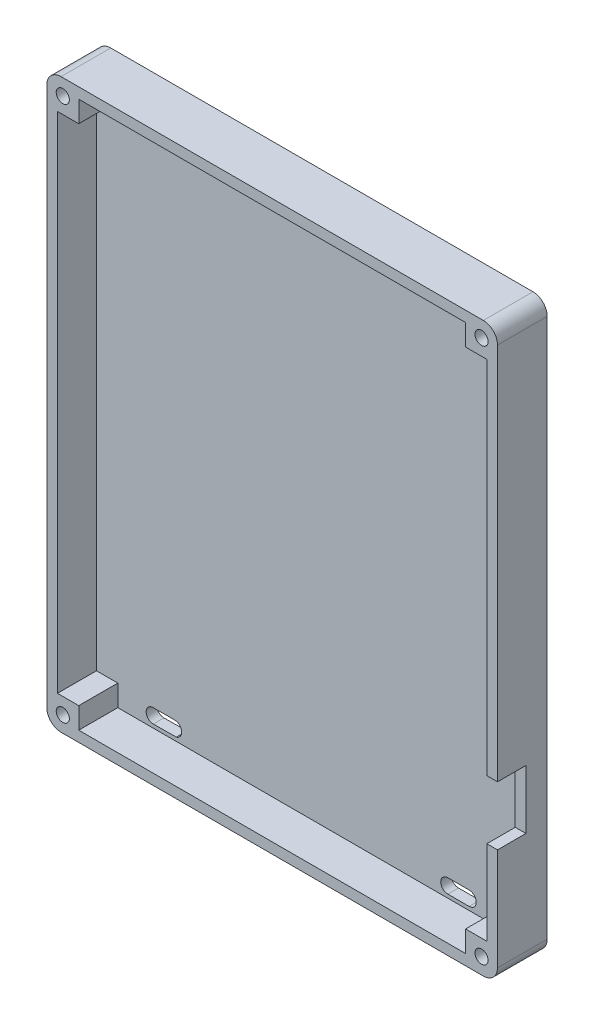
SolidWorks part; units mm, degrees
ref_plane "Ön Düzlem" through (0, 0, 0) normal (0, 0, 1) x (1, 0, 0)
ref_plane "Üst Düzlem" through (0, 0, 0) normal (0, 1, 0) x (1, 0, 0)
ref_plane "Sağ Düzlem" through (0, 0, 0) normal (1, 0, 0) x (0, 0, -1)
sketch "Çizim1" plane through (0, 0, 0) normal (0, 0, 1) x (1, 0, 0)
  line L1 (-31.75, -40) -> (31.75, -40)
  line L2 (-31.75, -40) -> (-31.75, 40)
  line L3 (-31.75, 40) -> (31.75, 40)
  line L4 (31.75, -40) -> (31.75, 40)
  line L5 (-31.75, -40) -> (31.75, 40) construction
  line L6 (-31.75, 40) -> (31.75, -40) construction
  point P0 (0, 0)
  dimension "D1" = 63.5
  dimension "D2" = 80
extrude "Yükseklik-Ekstrüzyon1" add sketch "Çizim1" along normal blind 1.5
sketch "Çizim2" plane through (0, 0, 1.5) normal (0, 0, 1) x (1, 0, 0)
  line L0 (31.75, -40) -> (31.75, 40) construction
  line L1 (-30.25, -38.5) -> (30.25, -38.5)
  line L2 (-30.25, -38.5) -> (-30.25, 38.5)
  line L3 (-30.25, 38.5) -> (30.25, 38.5)
  line L4 (30.25, -38.5) -> (30.25, 38.5)
  line L5 (-30.25, -38.5) -> (30.25, 38.5) construction
  line L6 (-30.25, 38.5) -> (30.25, -38.5) construction
  line L7 (31.75, 40) -> (-31.75, 40) construction
  line L9 (-31.75, -40) -> (31.75, -40)
  line L10 (-31.75, -40) -> (-31.75, 40)
  line L11 (-31.75, 40) -> (31.75, 40)
  line L12 (31.75, -40) -> (31.75, 40)
  line L13 (-31.75, -40) -> (31.75, 40) construction
  line L14 (-31.75, 40) -> (31.75, -40) construction
  point P0 (0, 0)
  point P10 (0, 0)
  dimension "D1" = 1.5
  dimension "D2" = 1.5
extrude "Yükseklik-Ekstrüzyon2" add sketch "Çizim2" along normal blind 5.5
fillet "Radyus1" radius 2 4 edges at (-31.75, -40, 3.5) (31.75, -40, 3.5) (31.75, 40, 3.5) (-31.75, 40, 3.5)
sketch "Çizim6" plane through (0, 0, 0) normal (0, 0, -1) x (-1, 0, 0)
  line L0 (-3.5355, 18.5355) -> (-5.3033, 20.3033)
  line L1 (-3.5355, 11.4645) -> (-5.3033, 9.6967)
  line L2 (3.5355, 18.5355) -> (5.3033, 20.3033)
  line L3 (3.5355, 11.4645) -> (5.3033, 9.6967)
  line L4 (-8.8388, 23.8388) -> (-10.6066, 25.6066)
  line L5 (-14.1421, 29.1421) -> (-15.9099, 30.9099)
  line L6 (-8.8388, 6.1612) -> (-10.6066, 4.3934)
  line L7 (-14.1421, 0.8579) -> (-15.9099, -0.9099)
  line L8 (8.8388, 23.8388) -> (10.6066, 25.6066)
  line L9 (14.1421, 29.1421) -> (15.9099, 30.9099)
  line L10 (14.1421, 0.8579) -> (15.9099, -0.9099)
  line L11 (8.8388, 6.1612) -> (10.6066, 4.3934)
  arc A0 (-15.9099, 30.9099) -> (-15.9099, -0.9099) centre (0, 15) ccw
  arc A1 (-14.1421, 29.1421) -> (-14.1421, 0.8579) centre (0, 15) ccw
  arc A2 (-10.6066, 25.6066) -> (-10.6066, 4.3934) centre (0, 15) ccw
  arc A3 (-8.8388, 23.8388) -> (-8.8388, 6.1612) centre (0, 15) ccw
  arc A4 (-5.3033, 20.3033) -> (-5.3033, 9.6967) centre (0, 15) ccw
  arc A5 (-3.5355, 18.5355) -> (-3.5355, 11.4645) centre (0, 15) ccw
  arc A6 (15.9099, -0.9099) -> (15.9099, 30.9099) centre (0, 15) ccw
  arc A7 (14.1421, 0.8579) -> (14.1421, 29.1421) centre (0, 15) ccw
  arc A8 (10.6066, 4.3934) -> (10.6066, 25.6066) centre (0, 15) ccw
  arc A9 (8.8388, 6.1612) -> (8.8388, 23.8388) centre (0, 15) ccw
  arc A10 (5.3033, 9.6967) -> (5.3033, 20.3033) centre (0, 15) ccw
  arc A11 (3.5355, 11.4645) -> (3.5355, 18.5355) centre (0, 15) ccw
  dimension "D2" = 45
  dimension "D3" = 40
  dimension "D4" = 30
  dimension "D5" = 25
  dimension "D6" = 15
  dimension "D7" = 10
  dimension "D1" = 15
extrude "Kes-Ekstrüzyon2" cut sketch "Çizim6" against normal blind 0.5
sketch "Çizim8" plane through (0, 0, 1.5) normal (0, 0, 1) x (1, 0, 0)
  line L0 (-51.4663, 0) -> (79.7106, 0) construction
  line L1 (-30.25, 38.5) -> (-27.25, 38.5)
  line L2 (-30.25, 38.5) -> (-30.25, 35.5)
  line L3 (-30.25, 35.5) -> (-27.25, 35.5)
  line L4 (-27.25, 38.5) -> (-27.25, 35.5)
  line L5 (30.25, 38.5) -> (27.25, 38.5)
  line L6 (30.25, 38.5) -> (30.25, 35.5)
  line L7 (30.25, 35.5) -> (27.25, 35.5)
  line L8 (27.25, 38.5) -> (27.25, 35.5)
  line L9 (30.25, -35.5) -> (27.25, -35.5)
  line L10 (27.25, -38.5) -> (27.25, -35.5)
  line L11 (30.25, -38.5) -> (27.25, -38.5)
  line L12 (30.25, -38.5) -> (30.25, -35.5)
  line L13 (-30.25, -35.5) -> (-27.25, -35.5)
  line L14 (-27.25, -38.5) -> (-27.25, -35.5)
  line L15 (-30.25, -38.5) -> (-27.25, -38.5)
  line L16 (-30.25, -38.5) -> (-30.25, -35.5)
  dimension "D1" = 3
  dimension "D2" = 3
  dimension "D3" = 3
  dimension "D4" = 3
extrude "Yükseklik-Ekstrüzyon4" add sketch "Çizim8" along normal blind 5.5
sketch "Çizim9" plane through (0, 0, 7) normal (0, 0, 1) x (1, 0, 0)
  line L0 (-31.75, 38) -> (-31.75, -38) construction
  line L1 (29.75, 40) -> (-29.75, 40) construction
  line L2 (0, 57.2816) -> (0, -54.0955) construction
  line L3 (-49.4799, 0) -> (71.8306, 0) construction
  circle A0 centre (-29.5, 37.75) radius 0.925
  circle A1 centre (29.5, 37.75) radius 0.925
  circle A2 centre (29.5, -37.75) radius 0.925
  circle A3 centre (-29.5, -37.75) radius 0.925
  dimension "D1" = 2.25
  dimension "D2" = 2.25
  dimension "D3" = 1.85
extrude "Kes-Ekstrüzyon4" cut sketch "Çizim9" against normal blind 5
sketch "Çizim10" plane through (31.75, 0, 0) normal (1, 0, 0) x (0, 0, -1)
  line L0 (-7, -35.5) -> (-1.5, -35.5) construction
  line L1 (-7, -23.6) -> (-3, -23.6)
  line L2 (-7, -23.6) -> (-7, -15.3)
  line L3 (-7, -15.3) -> (-3, -15.3)
  line L4 (-3, -23.6) -> (-3, -15.3)
  line L5 (0, -38) -> (0, 38) construction
  line L6 (-7, -38) -> (-7, 38) construction
  dimension "D1" = 11.9
  dimension "D2" = 0
  dimension "D3" = 3
  dimension "D4" = 8.3
extrude "Kes-Ekstrüzyon5" cut sketch "Çizim10" against normal blind 2
sketch "Çizim11" plane through (0, 0, 1.5) normal (0, 0, 1) x (1, 0, 0)
  line L0 (-27.25, -38.5) -> (-27.25, -35.5) construction
  line L1 (-27.25, -38.5) -> (27.25, -38.5) construction
  line L2 (-22.25, -36) -> (-19.25, -36)
  line L3 (-22.25, -38) -> (-19.0075, -37.9701)
  line L4 (27.25, -35.5) -> (27.25, -38.5) construction
  line L5 (19.25, -36) -> (22.25, -36)
  line L6 (19.25, -38) -> (22.25, -38)
  arc A0 (-22.25, -36) -> (-22.25, -38) centre (-22.25, -37) ccw
  arc A1 (-19.0075, -37.9701) -> (-19.25, -36) centre (-19.25, -37) ccw
  arc A2 (22.25, -38) -> (22.25, -36) centre (22.25, -37) ccw
  arc A3 (19.25, -36) -> (19.25, -38) centre (19.25, -37) ccw
  dimension "D1" = 2
  dimension "D2" = 5
  dimension "D3" = 1.5
  dimension "D4" = 2
  dimension "D5" = 3
  dimension "D6" = 5
  dimension "D7" = 3
extrude "Kes-Ekstrüzyon6" cut sketch "Çizim11" against normal blind 1.5
